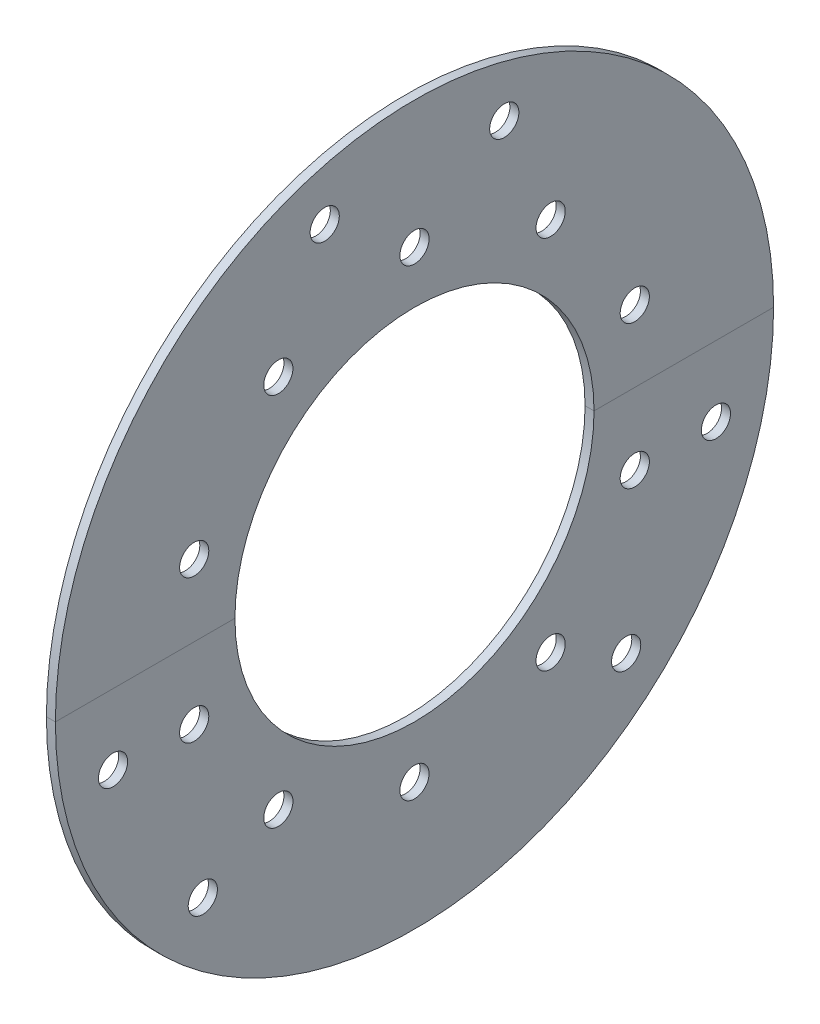
SolidWorks part; units mm, degrees
ref_plane "Front Plane" through (0, 0, 0) normal (0, 0, 1) x (1, 0, 0)
ref_plane "Top Plane" through (0, 0, 0) normal (0, 1, 0) x (1, 0, 0)
ref_plane "Right Plane" through (0, 0, 0) normal (1, 0, 0) x (0, 0, -1)
sketch "Sketch1" plane through (0, 0, 0) normal (1, 0, 0) x (0, 0, -1)
  line L0 (0, 0) -> (0, 66) construction
  line L1 (-20, 66) -> (20, 66) construction
  line L2 (0, 0) -> (0, 51.6) construction
  circle A0 centre (0, 0) radius 80
  circle A1 centre (0, 0) radius 40
  circle A2 centre (30.3297, 41.7453) radius 3.25
  circle A3 centre (49.0745, 15.9453) radius 3.25
  circle A4 centre (49.0745, -15.9453) radius 3.25
  circle A5 centre (30.3297, -41.7453) radius 3.25
  circle A6 centre (0, -51.6) radius 3.25
  circle A7 centre (-30.3297, -41.7453) radius 3.25
  circle A8 centre (-49.0745, -15.9453) radius 3.25
  circle A10 centre (-49.0745, 15.9453) radius 3.25
  circle A11 centre (-30.3297, 41.7453) radius 3.25
  circle A12 centre (0, 51.6) radius 3.25
  circle A22 centre (-20, 66) radius 3.25
  circle A23 centre (20, 66) radius 3.25
  circle A24 centre (67.1577, -15.6795) radius 3.25
  circle A25 centre (47.1577, -50.3205) radius 3.25
  circle A26 centre (-47.1577, -50.3205) radius 3.25
  circle A27 centre (-67.1577, -15.6795) radius 3.25
  point P6 (-39.2312, -26.4851)
  point P7 (0, 0)
  point P8 (0, 0)
  point P18 (10.2095, 1.2137)
  point P19 (0, 0)
  point P29 (0, 0)
  point P30 (0, 0)
  point P31 (0, 0)
  point P32 (0, 0)
  point P33 (1.5283, 11.2308)
  point P37 (0, 66)
  point P51 (0, 0)
  dimension "OuterDia" = 160
  dimension "InnerDia" = 80
  dimension "D5" = 6.5
  dimension "D7" = 6.5
  dimension "BoltHoleDia" = 6.5
  dimension "OuterHoleOffset" = 66
  dimension "OuterHoleSpacing" = 40
  dimension "InnerHoleOffset" = 51.6
  dimension "D8" = 3
  dimension "D10" = 10
extrude "Boss-Extrude1" add sketch "Sketch1" along normal blind 2
ref_plane "Plane1" through (0, 0, 0) normal (0, 1, 0) x (1, 0, 0)
split "Split1" trim tools "Plane1" bodies to split 102 resulting bodies 103 104
equation "\"D5@Sketch1\"=\"BoltHoleDia@Sketch1\""
equation "\"D7@Sketch1\"=\"BoltHoleDia@Sketch1\""
